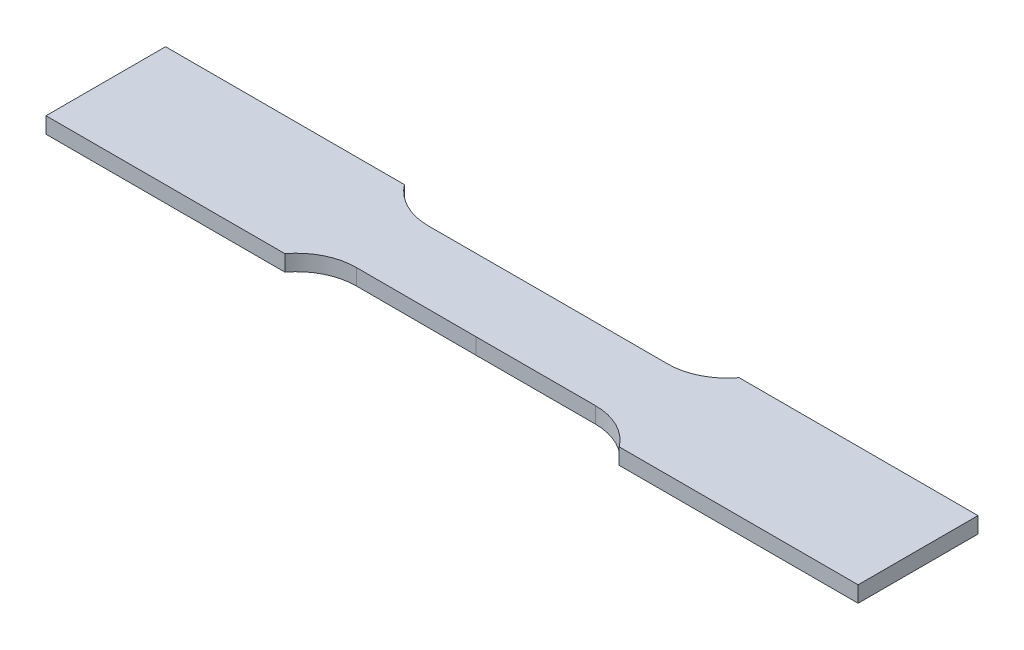
SolidWorks part; units mm, degrees
ref_plane "Front Plane" through (0, 0, 0) normal (0, 0, 1) x (1, 0, 0)
ref_plane "Top Plane" through (0, 0, 0) normal (0, 1, 0) x (1, 0, 0)
ref_plane "Right Plane" through (0, 0, 0) normal (1, 0, 0) x (0, 0, -1)
sketch "Sketch1" plane through (0, 0, 0) normal (0, 1, 0) x (1, 0, 0)
  line L3 (25, 7.555) -> (0, 7.57)
  line L4 (0, 7.57) -> (-25, 7.535)
  line L5 (-25, -7.535) -> (0, -7.57)
  line L6 (0, -7.57) -> (25, -7.555)
  line L7 (0, 7.57) -> (0, -7.57) construction
  line L8 (-25, 0) -> (25, 0) construction
  line L9 (25, 7.555) -> (25, 12.545) construction
  line L10 (-35, 12.5117) -> (-25, 12.5117) construction
  line L11 (-25, 12.5117) -> (-25, 7.535) construction
  line L12 (-25, -12.5117) -> (-25, -7.535) construction
  line L13 (-35, 12.5117) -> (-85, 12.5117)
  line L15 (-35, -12.5117) -> (-85, -12.5117)
  line L16 (-85, 12.5117) -> (-85, -12.5117)
  line L17 (25, 12.545) -> (35, 12.545) construction
  line L18 (-35, -12.5117) -> (-25, -12.5117) construction
  line L19 (-25, 7.535) -> (-25, -7.535) construction
  line L20 (25, -7.555) -> (25, 7.555) construction
  line L22 (25, -7.555) -> (25, -12.545) construction
  line L23 (25, -12.545) -> (35, -12.545) construction
  line L24 (35, 12.545) -> (85, 12.545)
  line L26 (35, -12.545) -> (85, -12.545)
  line L27 (85, 12.545) -> (85, -12.545)
  arc A0 (-35, 12.5117) -> (-25, 7.535) centre (-25.0175, 20.035) ccw
  arc A1 (-35, -12.5117) -> (-25, -7.535) centre (-25.0175, -20.035) cw
  arc A2 (35, -12.545) -> (25, -7.555) centre (25.0075, -20.055) ccw
  arc A3 (35, 12.545) -> (25, 7.555) centre (25.0075, 20.055) cw
  dimension "D5" = 25
  dimension "D9" = 25
  dimension "D4" = 15.14
  dimension "D6" = 10
  dimension "D8" = 50
  dimension "D1" = 15.07
  dimension "D2" = 15.11
  dimension "D3" = 50
  dimension "D10" = 10
  dimension "D11" = 50
extrude "Boss-Extrude2" add sketch "Sketch1" along normal blind 3.357 contours L24 A3 L3 L4 A0 L13 L16 L15 A1 L5 L6 A2 L26 L27
equation "\"D5@Sketch1\"=12.5*2"
equation "\"D9@Sketch1\"=12.5*2"
